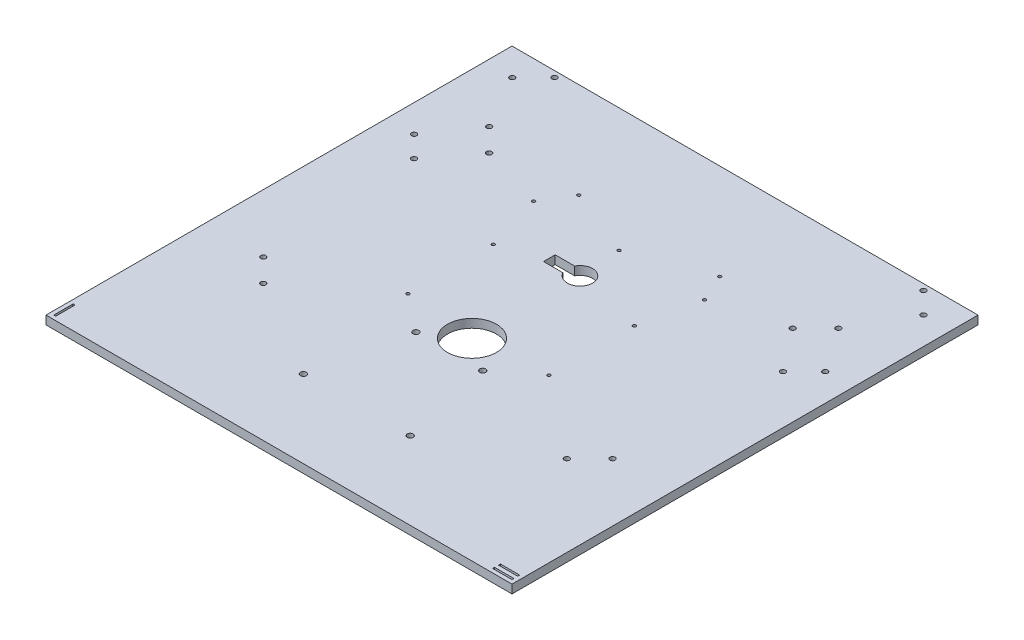
SolidWorks part; units mm, degrees
ref_plane "Front Plane" through (0, 0, 0) normal (0, 0, 1) x (1, 0, 0)
ref_plane "Top Plane" through (0, 0, 0) normal (0, 1, 0) x (1, 0, 0)
ref_plane "Right Plane" through (0, 0, 0) normal (1, 0, 0) x (0, 0, -1)
ref_plane "Plane1" through (0, 0, 0) normal (0, -1, 0) x (1, 0, 0)
sketch "Sketch1" plane through (0, 0, 0) normal (0, -1, 0) x (1, 0, 0)
  line L0 (3.81, -2.54) -> (3.81, -15.24)
  line L1 (3.81, -15.24) -> (2.54, -15.24)
  line L2 (2.54, -15.24) -> (2.54, -2.54)
  line L3 (2.54, -2.54) -> (3.81, -2.54)
  line L4 (289.56, -3.81) -> (289.56, -2.54)
  line L5 (289.56, -2.54) -> (302.26, -2.54)
  line L6 (302.26, -2.54) -> (302.26, -3.81)
  line L7 (302.26, -3.81) -> (289.56, -3.81)
  line L8 (289.56, -7.62) -> (289.56, -6.35)
  line L9 (289.56, -6.35) -> (302.26, -6.35)
  line L10 (302.26, -6.35) -> (302.26, -7.62)
  line L11 (302.26, -7.62) -> (289.56, -7.62)
  line L12 (132.3768, -200.66) -> (132.3768, -193.04)
  line L13 (132.3768, -193.04) -> (145.0768, -193.04)
  line L14 (145.0768, -200.66) -> (132.3768, -200.66)
  line L15 (304.8, -304.8) -> (304.8, 0)
  line L16 (304.8, 0) -> (0, 0)
  line L17 (0, 0) -> (0, -304.8)
  line L18 (0, -304.8) -> (304.8, -304.8)
  circle A0 centre (152.48, -126.1263) radius 16.002
  circle A1 centre (31.75, -300.8321) radius 1.7
  circle A2 centre (17.9388, -287.0209) radius 1.7
  circle A3 centre (273.05, -300.8321) radius 1.7
  circle A4 centre (286.8612, -287.0209) radius 1.7
  circle A5 centre (286.8612, -222.7817) radius 1.7
  circle A6 centre (273.05, -208.9705) radius 1.7
  circle A7 centre (31.75, -208.9705) radius 1.7
  circle A8 centre (17.9388, -222.7817) radius 1.7
  circle A9 centre (38.1788, -103.933) radius 1.7
  circle A10 centre (53.133, -88.9788) radius 1.7
  circle A11 centre (251.667, -88.9788) radius 1.7
  circle A12 centre (266.6212, -103.933) radius 1.7
  circle A13 centre (266.6212, -251.667) radius 1.7
  circle A14 centre (251.667, -236.7127) radius 1.7
  circle A15 centre (53.133, -236.7127) radius 1.7
  circle A16 centre (38.1788, -251.667) radius 1.7
  circle A17 centre (130.6519, -111.328) radius 1.96
  circle A18 centre (174.3081, -111.328) radius 1.96
  circle A19 centre (187.405, -50.8216) radius 1.96
  circle A20 centre (117.555, -50.8216) radius 1.96
  arc A21 (145.0768, -193.04) -> (145.0768, -200.66) centre (152.4, -196.85) cw
  circle A22 centre (206.7, -223.995) radius 1.016
  circle A23 centre (150.82, -223.995) radius 1.016
  circle A24 centre (94.94, -223.995) radius 1.016
  circle A25 centre (106.3, -242.18) radius 1.016
  circle A26 centre (106.3, -186.3) radius 1.016
  circle A27 centre (106.3, -130.42) radius 1.016
  circle A28 centre (198.5, -130.42) radius 1.016
  circle A29 centre (198.5, -186.3) radius 1.016
  circle A30 centre (198.5, -242.18) radius 1.016
extrude "Boss-Extrude1" add sketch "Sketch1" against normal blind 5.588
